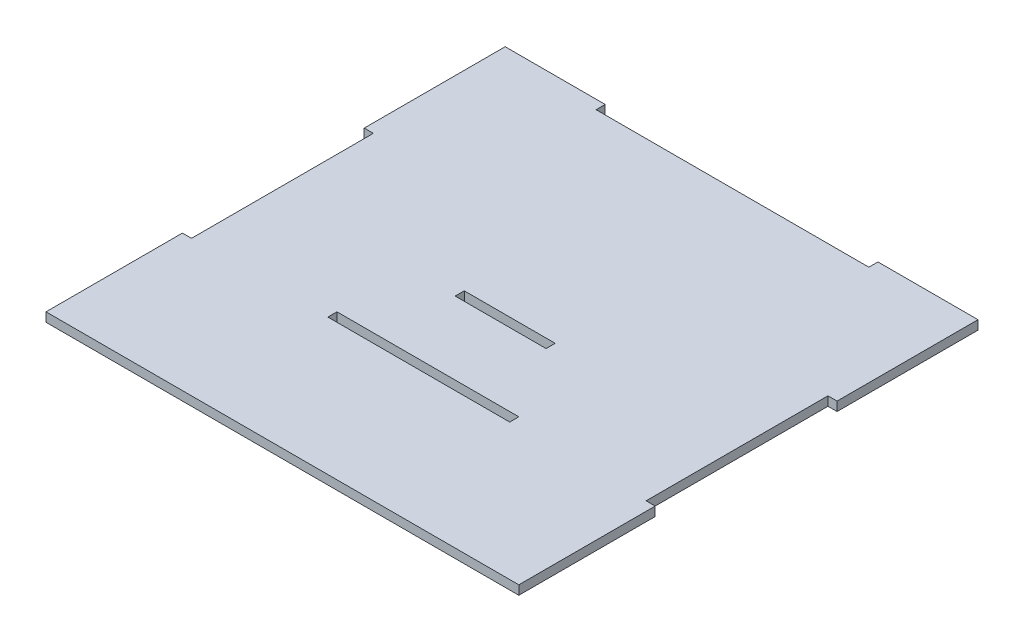
SolidWorks part; units mm, degrees
ref_plane "前视基准面" through (0, 0, 0) normal (0, 0, 1) x (1, 0, 0)
ref_plane "上视基准面" through (0, 0, 0) normal (0, 1, 0) x (1, 0, 0)
ref_plane "右视基准面" through (0, 0, 0) normal (1, 0, 0) x (0, 0, -1)
sketch "草图1" plane through (0, 0, 0) normal (0, 1, 0) x (1, 0, 0)
  line L0 (0, 0) -> (0, 101)
  line L1 (0, 0) -> (104, 0)
  line L2 (0, 101) -> (104, 101)
  line L3 (104, 0) -> (104, 101)
  line L8 (0, 70) -> (0, 30)
  line L9 (0, 70) -> (2, 70)
  line L10 (0, 30) -> (2, 30)
  line L11 (2, 70) -> (2, 30)
  line L12 (102, 70) -> (104, 70)
  line L13 (102, 70) -> (102, 30)
  line L14 (104, 70) -> (104, 30)
  line L15 (102, 30) -> (104, 30)
  line L16 (22, 101) -> (22, 99)
  line L17 (22, 101) -> (82, 101)
  line L18 (22, 99) -> (82, 99)
  line L19 (82, 101) -> (82, 99)
  line L24 (42, 48) -> (42, 50)
  line L25 (42, 48) -> (62, 48)
  line L26 (42, 50) -> (62, 50)
  line L27 (62, 48) -> (62, 50)
  line L28 (32, 30) -> (32, 32)
  line L29 (32, 30) -> (72, 30)
  line L30 (32, 32) -> (72, 32)
  line L31 (72, 30) -> (72, 32)
  point P0 (0, 30)
  point P3 (0, 0)
  point P4 (0, 0)
  point P5 (0, 70)
  point P6 (2, 70)
  point P7 (2, 30)
  point P8 (102, 30)
  point P12 (102, 70)
  point P13 (104, 30)
  point P16 (104, 70)
  point P17 (0, 0)
  point P24 (0, 0)
  point P25 (0, 0)
  point P28 (0, 0)
  point P29 (42, 50)
  point P32 (62, 48)
  point P33 (62, 50)
  point P36 (0, 0)
  point P39 (42, 48)
  point P40 (0, 0)
  point P41 (0, 0)
extrude "凸台-拉伸2" add sketch "草图1" along normal blind 2
